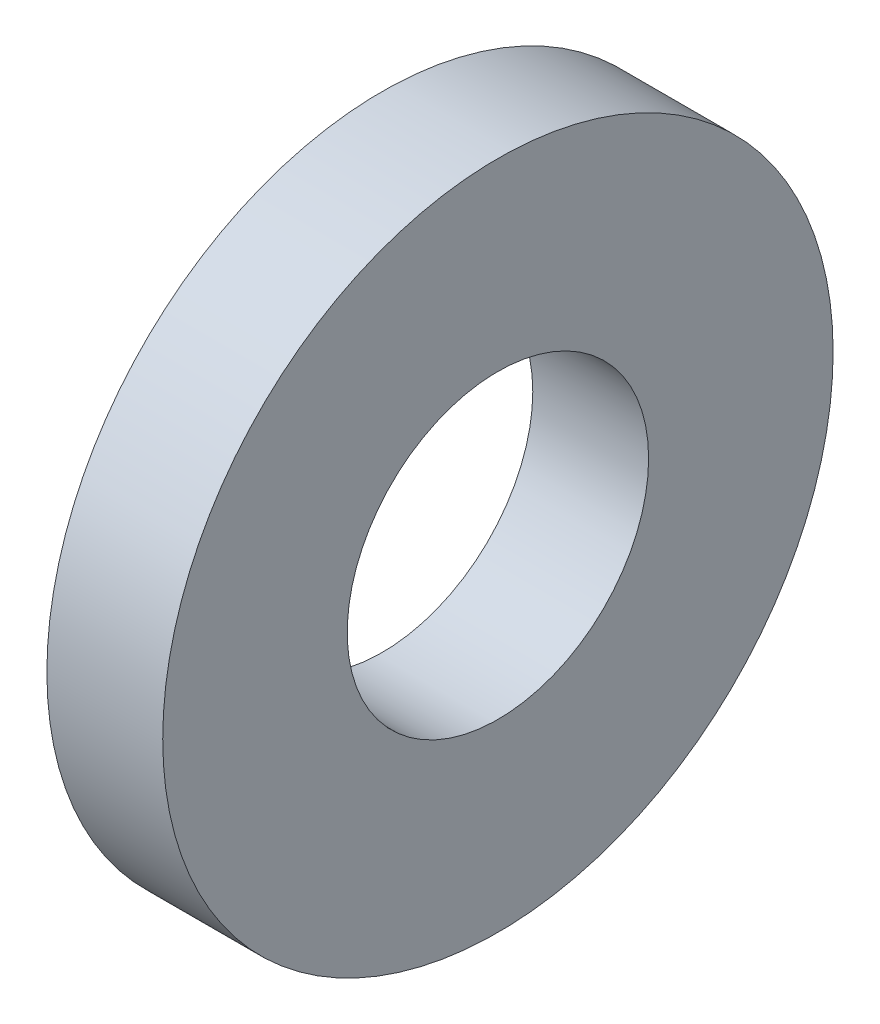
SolidWorks part; units mm, degrees
ref_plane "Front Plane" through (0, 0, 0) normal (0, 0, 1) x (1, 0, 0)
ref_plane "Top Plane" through (0, 0, 0) normal (0, 1, 0) x (1, 0, 0)
ref_plane "Right Plane" through (0, 0, 0) normal (1, 0, 0) x (0, 0, -1)
sketch "Sketch1" plane through (0, 0, 0) normal (1, 0, 0) x (0, 0, -1)
  circle A0 centre (0, 0) radius 7.9375
  circle A1 centre (0, 0) radius 3.5687
  dimension "OD" = 15.875
  dimension "ID" = 7.1374
extrude "Boss-Extrude1" add sketch "Sketch1" along normal blind 2.7432
